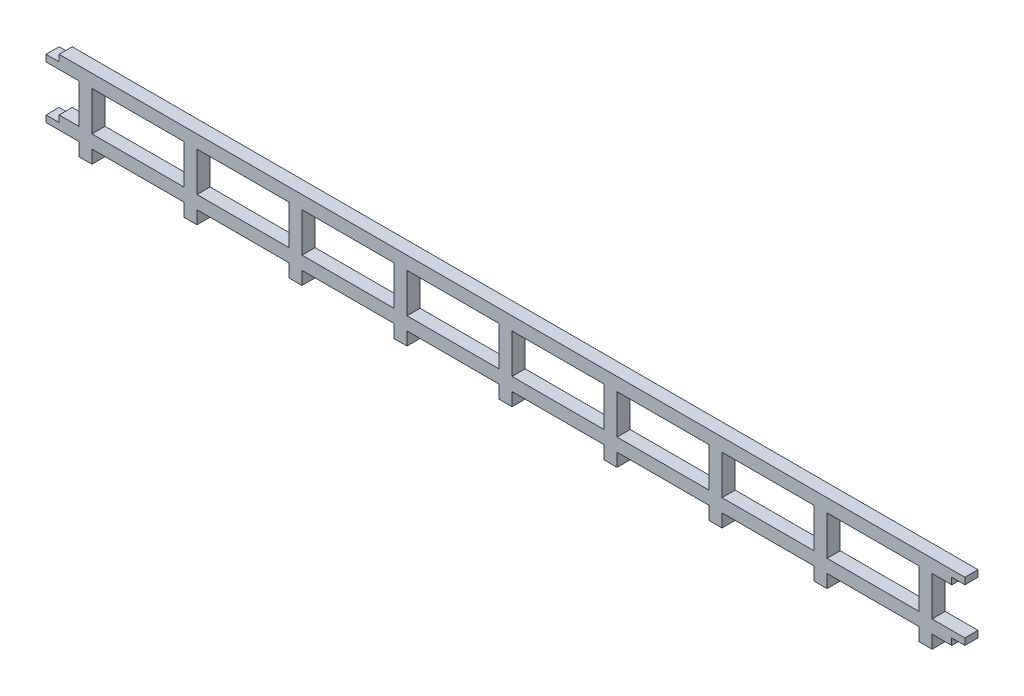
SolidWorks part; units mm, degrees
ref_plane "Front Plane" through (0, 0, 0) normal (0, 0, 1) x (1, 0, 0)
ref_plane "Top Plane" through (0, 0, 0) normal (0, 1, 0) x (1, 0, 0)
ref_plane "Right Plane" through (0, 0, 0) normal (1, 0, 0) x (0, 0, -1)
sketch "Sketch1" plane through (0, 0, 0) normal (0, 0, 1) x (1, 0, 0)
  line L88 (181.5, 30) -> (202.5, 30)
  line L89 (202.5, 30) -> (202.5, 39)
  line L90 (202.5, 39) -> (181.5, 39)
  line L91 (181.5, 39) -> (181.5, 30)
  line L92 (157.5, 30) -> (178.5, 30)
  line L93 (178.5, 30) -> (178.5, 39)
  line L94 (178.5, 39) -> (157.5, 39)
  line L95 (157.5, 39) -> (157.5, 30)
  line L96 (133.5, 30) -> (154.5, 30)
  line L97 (154.5, 30) -> (154.5, 39)
  line L98 (154.5, 39) -> (133.5, 39)
  line L99 (133.5, 39) -> (133.5, 30)
  line L100 (109.5, 30) -> (130.5, 30)
  line L101 (130.5, 30) -> (130.5, 39)
  line L102 (130.5, 39) -> (109.5, 39)
  line L103 (109.5, 39) -> (109.5, 30)
  line L104 (85.5, 30) -> (106.5, 30)
  line L105 (106.5, 30) -> (106.5, 39)
  line L106 (106.5, 39) -> (85.5, 39)
  line L107 (85.5, 39) -> (85.5, 30)
  line L108 (61.5, 30) -> (82.5, 30)
  line L109 (82.5, 30) -> (82.5, 39)
  line L110 (82.5, 39) -> (61.5, 39)
  line L111 (61.5, 39) -> (61.5, 30)
  line L112 (37.5, 30) -> (58.5, 30)
  line L113 (58.5, 30) -> (58.5, 39)
  line L114 (58.5, 39) -> (37.5, 39)
  line L115 (37.5, 39) -> (37.5, 30)
  line L116 (13.5, 30) -> (34.5, 30)
  line L117 (34.5, 30) -> (34.5, 39)
  line L118 (34.5, 39) -> (13.5, 39)
  line L119 (13.5, 39) -> (13.5, 30)
  line L120 (178.5, 24) -> (181.5, 24)
  line L121 (181.5, 24) -> (181.5, 27)
  line L122 (181.5, 27) -> (202.5, 27)
  line L123 (202.5, 27) -> (202.5, 24)
  line L124 (202.5, 24) -> (205.5, 24)
  line L125 (205.5, 24) -> (205.5, 27)
  line L126 (205.5, 27) -> (210, 27)
  line L127 (210, 27) -> (210, 28.5)
  line L128 (210, 28.5) -> (213, 28.5)
  line L129 (213, 28.5) -> (213, 30)
  line L130 (213, 30) -> (205.5, 30)
  line L131 (205.5, 30) -> (205.5, 39)
  line L132 (205.5, 39) -> (210, 39)
  line L133 (210, 39) -> (210, 40.5)
  line L134 (210, 40.5) -> (213, 40.5)
  line L135 (213, 40.5) -> (213, 42)
  line L136 (213, 42) -> (6, 42)
  line L137 (6, 42) -> (6, 40.5)
  line L138 (6, 40.5) -> (3, 40.5)
  line L139 (3, 40.5) -> (3, 39)
  line L140 (3, 39) -> (10.5, 39)
  line L141 (10.5, 39) -> (10.5, 30)
  line L142 (10.5, 30) -> (6, 30)
  line L143 (6, 30) -> (6, 28.5)
  line L144 (6, 28.5) -> (3, 28.5)
  line L145 (3, 28.5) -> (3, 27)
  line L146 (3, 27) -> (10.5, 27)
  line L147 (10.5, 27) -> (10.5, 24)
  line L148 (10.5, 24) -> (13.5, 24)
  line L149 (13.5, 24) -> (13.5, 27)
  line L150 (13.5, 27) -> (34.5, 27)
  line L151 (34.5, 27) -> (34.5, 24)
  line L152 (34.5, 24) -> (37.5, 24)
  line L153 (37.5, 24) -> (37.5, 27)
  line L154 (37.5, 27) -> (58.5, 27)
  line L155 (58.5, 27) -> (58.5, 24)
  line L156 (58.5, 24) -> (61.5, 24)
  line L157 (61.5, 24) -> (61.5, 27)
  line L158 (61.5, 27) -> (82.5, 27)
  line L159 (82.5, 27) -> (82.5, 24)
  line L160 (82.5, 24) -> (85.5, 24)
  line L161 (85.5, 24) -> (85.5, 27)
  line L162 (85.5, 27) -> (106.5, 27)
  line L163 (106.5, 27) -> (106.5, 24)
  line L164 (106.5, 24) -> (109.5, 24)
  line L165 (109.5, 24) -> (109.5, 27)
  line L166 (109.5, 27) -> (130.5, 27)
  line L167 (130.5, 27) -> (130.5, 24)
  line L168 (130.5, 24) -> (133.5, 24)
  line L169 (133.5, 24) -> (133.5, 27)
  line L170 (133.5, 27) -> (154.5, 27)
  line L171 (154.5, 27) -> (154.5, 24)
  line L172 (154.5, 24) -> (157.5, 24)
  line L173 (157.5, 24) -> (157.5, 27)
  line L174 (157.5, 27) -> (178.5, 27)
  line L175 (178.5, 27) -> (178.5, 24)
extrude "Boss-Extrude1" add sketch "Sketch1" along normal blind 3
